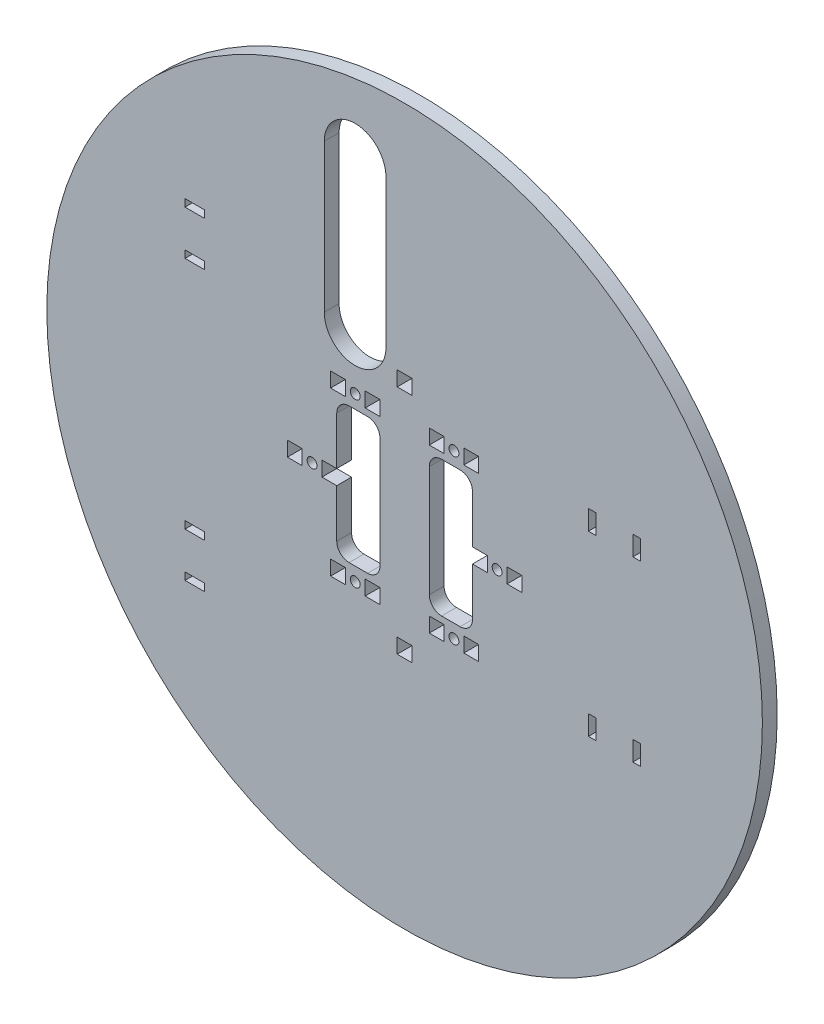
SolidWorks part; units mm, degrees
ref_plane "Front Plane" through (0, 0, 0) normal (0, 0, 1) x (1, 0, 0)
ref_plane "Top Plane" through (0, 0, 0) normal (0, 1, 0) x (1, 0, 0)
ref_plane "Right Plane" through (0, 0, 0) normal (1, 0, 0) x (0, 0, -1)
sketch "Esquisse1" plane through (0, 0, 0) normal (0, 0, 1) x (1, 0, 0)
  line L0 (-101.6649, 0) -> (103.0475, 0) construction
  line L1 (-94.3537, 33) -> (85.3468, 33) construction
  line L2 (-87.0426, -33) -> (91.8884, -33) construction
  line L3 (0, 77.9722) -> (0, -79.0253) construction
  line L4 (-3, -49.9099) -> (3, -49.9099)
  line L5 (-3, 49.9099) -> (3, 49.9099)
  line L6 (-3, 49.9099) -> (-3, 43.9099)
  line L7 (-3, 43.9099) -> (3, 43.9099)
  line L8 (3, 49.9099) -> (3, 43.9099)
  line L9 (-3, -49.9099) -> (-3, -43.9099)
  line L10 (-3, -43.9099) -> (3, -43.9099)
  line L11 (3, -49.9099) -> (3, -43.9099)
  line L18 (-34.6987, 36) -> (34.6987, 36) construction
  line L19 (-34.6987, 36) -> (-34.6987, 30) construction
  line L20 (-34.6987, 30) -> (34.6987, 30) construction
  line L21 (34.6987, 36) -> (34.6987, 30) construction
  line L22 (-49.9099, 3) -> (49.9099, 3) construction
  line L23 (-49.9099, 3) -> (-49.9099, -3) construction
  line L24 (-49.9099, -3) -> (49.9099, -3) construction
  line L25 (49.9099, 3) -> (49.9099, -3) construction
  circle A0 centre (0, 0) radius 145
  circle A1 centre (0, 0) radius 50 construction
  point P10 (0, 49.9099)
  point P25 (0, 0)
  point P26 (0, 0)
  line B0 (-41.5, 0) -> (-33.5, 0) construction
  line B1 (-41.5, 3) -> (-47.5, 3)
  line B2 (-41.5, 3) -> (-41.5, -3)
  line B3 (-41.5, -3) -> (-47.5, -3)
  line B4 (-47.5, 3) -> (-47.5, -3)
  line B5 (-33.5, 3) -> (-27.5, 3)
  line B6 (-33.5, 3) -> (-33.5, -3)
  line B7 (-33.5, -3) -> (-27.5, -3)
  line B8 (-27.5, 3) -> (-27.5, -3)
  line B9 (-37.5, 0) -> (-37.5, 3.6632) construction
  circle B10 centre (-37.5, 0) radius 2
  line B11 (-24, -33) -> (-16, -33) construction
  line B12 (-24, -30) -> (-30, -30)
  line B13 (-24, -30) -> (-24, -36)
  line B14 (-24, -36) -> (-30, -36)
  line B15 (-30, -30) -> (-30, -36)
  line B16 (-16, -30) -> (-10, -30)
  line B17 (-16, -30) -> (-16, -36)
  line B18 (-16, -36) -> (-10, -36)
  line B19 (-10, -30) -> (-10, -36)
  line B20 (-20, -33) -> (-20, -29.3368) construction
  circle B21 centre (-20, -33) radius 2
  line B22 (16, -33) -> (24, -33) construction
  line B23 (16, -30) -> (10, -30)
  line B24 (16, -30) -> (16, -36)
  line B25 (16, -36) -> (10, -36)
  line B26 (10, -30) -> (10, -36)
  line B27 (24, -30) -> (30, -30)
  line B28 (24, -30) -> (24, -36)
  line B29 (24, -36) -> (30, -36)
  line B30 (30, -30) -> (30, -36)
  line B31 (20, -33) -> (20, -29.3368) construction
  circle B32 centre (20, -33) radius 2
  line B33 (16, 33) -> (24, 33) construction
  line B34 (16, 36) -> (10, 36)
  line B35 (16, 36) -> (16, 30)
  line B36 (16, 30) -> (10, 30)
  line B37 (10, 36) -> (10, 30)
  line B38 (24, 36) -> (30, 36)
  line B39 (24, 36) -> (24, 30)
  line B40 (24, 30) -> (30, 30)
  line B41 (30, 36) -> (30, 30)
  line B42 (20, 33) -> (20, 36.6632) construction
  circle B43 centre (20, 33) radius 2
  line B44 (-24, 33) -> (-16, 33) construction
  line B45 (-24, 36) -> (-30, 36)
  line B46 (-24, 36) -> (-24, 30)
  line B47 (-24, 30) -> (-30, 30)
  line B48 (-30, 36) -> (-30, 30)
  line B49 (-16, 36) -> (-10, 36)
  line B50 (-16, 36) -> (-16, 30)
  line B51 (-16, 30) -> (-10, 30)
  line B52 (-10, 36) -> (-10, 30)
  line B53 (-20, 33) -> (-20, 36.6632) construction
  circle B54 centre (-20, 33) radius 2
  line B55 (33.5, 0) -> (41.5, 0) construction
  line B56 (33.5, 3) -> (27.5, 3)
  line B57 (33.5, 3) -> (33.5, -3)
  line B58 (33.5, -3) -> (27.5, -3)
  line B59 (27.5, 3) -> (27.5, -3)
  line B60 (41.5, 3) -> (47.5, 3)
  line B61 (41.5, 3) -> (41.5, -3)
  line B62 (41.5, -3) -> (47.5, -3)
  line B63 (47.5, 3) -> (47.5, -3)
  line B64 (37.5, 0) -> (37.5, 3.6632) construction
  circle B65 centre (37.5, 0) radius 2
  dimension "D1" = 290
  dimension "D2" = 100
  dimension "D3" = 33
  dimension "D4" = 33
  dimension "D5" = 40
  dimension "D6" = 20
  dimension "D7" = 75
  dimension "D8" = 37.5
  dimension "D9" = 6
  dimension "D10" = 6
sketch_block_instance "Trou M4 plots6 tol0mm-1"
sketch_block "Trou M4 plots6 tol0mm" parameters "D2"=4, "D1"=6, "D3"=6, "D4"=8
sketch_block_instance "Trou M4 plots6 tol0mm-2"
sketch_block_instance "Trou M4 plots6 tol0mm-3"
sketch_block_instance "Trou M4 plots6 tol0mm-4"
sketch_block_instance "Trou M4 plots6 tol0mm-5"
sketch_block_instance "Trou M4 plots6 tol0mm-6"
extrude "Boss.-Extru.1" add sketch "Esquisse1" along normal blind 6
sketch "Esquisse2" plane through (0, 0, 6) normal (0, 0, 1) x (1, 0, 0)
  line L0 (-27.5, -3) -> (-27.5, 3) construction
  line L1 (-27.5, 27.5) -> (-10, 27.5)
  line L2 (-27.5, 27.5) -> (-27.5, -27.5)
  line L3 (-27.5, -27.5) -> (-10, -27.5)
  line L4 (-10, 27.5) -> (-10, -27.5)
  line L5 (0, 34.5372) -> (0, -33.5037) construction
  line L6 (10, 27.5) -> (10, -27.5)
  line L7 (27.5, -27.5) -> (10, -27.5)
  line L8 (27.5, 27.5) -> (27.5, -27.5)
  line L9 (27.5, 27.5) -> (10, 27.5)
  line L11 (-22.0957, 0) -> (22.7418, 0) construction
  line L12 (77.5, 40) -> (77.5, 32)
  line L13 (85, 57.5) -> (-85, 57.5) construction
  line L14 (85, 57.5) -> (85, -57.5) construction
  line L15 (85, -57.5) -> (-85, -57.5) construction
  line L16 (-85, 57.5) -> (-85, -57.5) construction
  line L17 (95.5, 40) -> (92.5, 40)
  line L18 (95.5, 40) -> (95.5, 32)
  line L19 (95.5, 32) -> (92.5, 32)
  line L20 (92.5, 40) -> (92.5, 32)
  line L21 (74.5, 32) -> (77.5, 32)
  line L22 (74.5, 40) -> (74.5, 32)
  line L23 (74.5, 40) -> (77.5, 40)
  line L24 (74.5, -40) -> (77.5, -40)
  line L25 (74.5, -40) -> (74.5, -32)
  line L26 (77.5, -40) -> (77.5, -32)
  line L27 (74.5, -32) -> (77.5, -32)
  line L28 (95.5, -32) -> (92.5, -32)
  line L29 (92.5, -40) -> (92.5, -32)
  line L30 (95.5, -40) -> (92.5, -40)
  line L31 (95.5, -40) -> (95.5, -32)
  line L32 (-89, -49) -> (-89, -46)
  line L33 (-81, 67) -> (-89, 67)
  line L34 (-81, 67) -> (-81, 64)
  line L35 (-81, 64) -> (-89, 64)
  line L36 (-89, 67) -> (-89, 64)
  line L37 (-81, 49) -> (-89, 49)
  line L38 (-81, 49) -> (-81, 46)
  line L39 (-81, 46) -> (-89, 46)
  line L40 (-89, 49) -> (-89, 46)
  line L41 (-81, -46) -> (-89, -46)
  line L42 (-81, -49) -> (-81, -46)
  line L43 (-81, -49) -> (-89, -49)
  line L44 (-81, -64) -> (-89, -64)
  line L45 (-89, -67) -> (-89, -64)
  line L46 (-81, -67) -> (-81, -64)
  line L47 (-81, -67) -> (-89, -67)
  line L48 (-20.0551, 55.3627) -> (-20.0551, 115.3627) construction
  line L49 (-32.5551, 55.3627) -> (-32.5551, 115.3627)
  line L50 (-7.5551, 55.3627) -> (-7.5551, 115.3627)
  arc A1 (-32.5551, 55.3627) -> (-7.5551, 55.3627) centre (-20.0551, 55.3627) ccw
  arc A2 (-7.5551, 115.3627) -> (-32.5551, 115.3627) centre (-20.0551, 115.3627) ccw
  point P15 (-10, 0)
  point P16 (-22.0957, 55.3627)
  point P18 (-85, 0)
  point P23 (0, 57.5)
  point P40 (94, -32)
  point P57 (-85, 64)
  point P60 (-20.0551, 85.3627)
  dimension "D1" = 20
  dimension "D2" = 55
  dimension "D3" = 170
  dimension "D4" = 115
  dimension "D5" = 3
  dimension "D6" = 8
  dimension "D7" = 64
  dimension "D8" = 8
  dimension "D9" = 3
  dimension "D10" = 3
  dimension "D11" = 15
  dimension "D12" = 15
  dimension "D13" = 95
  dimension "D14" = 60
  dimension "D15" = 25
extrude "Enlèv. mat.-Extru.1" cut sketch "Esquisse2" against normal blind 6
fillet "Congé1" radius 5 8 edges at (27.5, -27.5, 3) (10, -27.5, 3) (27.5, 27.5, 3) (10, 27.5, 3) (-10, -27.5, 3) (-27.5, -27.5, 3) (-10, 27.5, 3) (-27.5, 27.5, 3)
